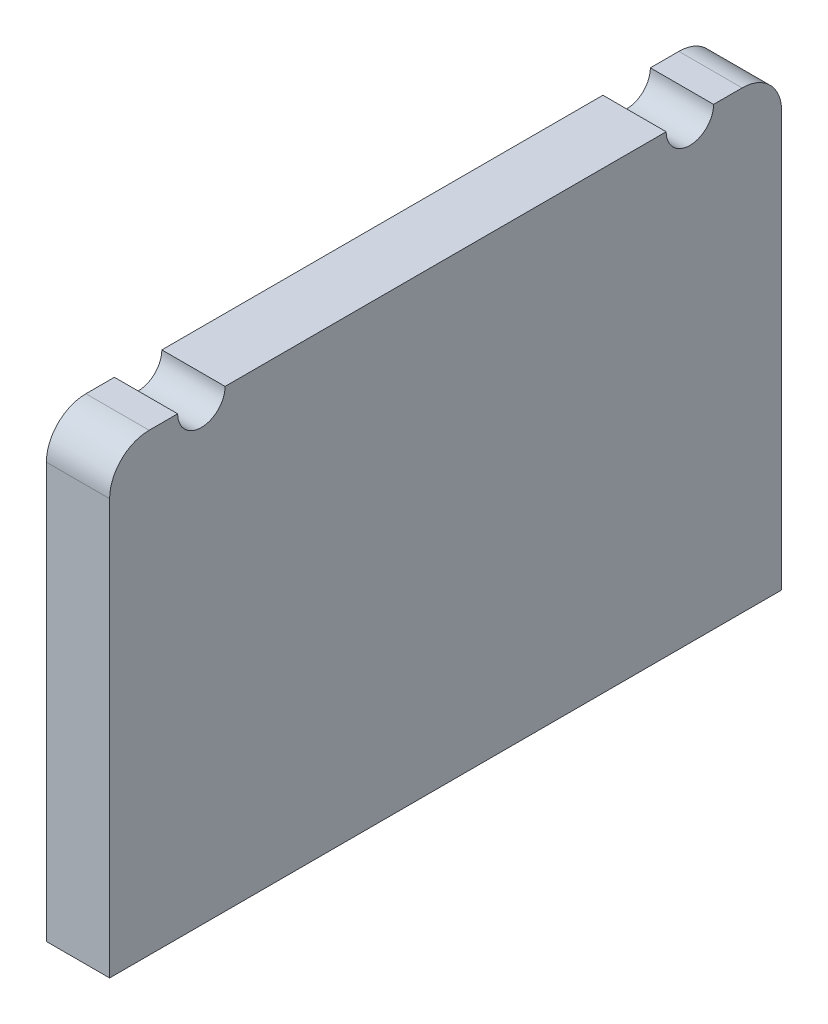
SolidWorks part; units mm, degrees
ref_plane "Front Plane" through (0, 0, 0) normal (0, 0, 1) x (1, 0, 0)
ref_plane "Top Plane" through (0, 0, 0) normal (0, 1, 0) x (1, 0, 0)
ref_plane "Right Plane" through (0, 0, 0) normal (1, 0, 0) x (0, 0, -1)
sketch "Sketch1" plane through (0, 0, 0) normal (1, 0, 0) x (0, 0, -1)
  line L1 (-53.975, -36.5125) -> (53.975, -36.5125)
  line L2 (-53.975, -36.5125) -> (-53.975, 30.1625)
  line L3 (-35.4259, 36.5125) -> (35.4259, 36.5125)
  line L4 (53.975, -36.5125) -> (53.975, 30.1625)
  line L5 (-53.975, -36.5125) -> (53.975, 36.5125) construction
  line L6 (-53.975, 36.5125) -> (53.975, -36.5125) construction
  line L7 (43.0459, 36.5125) -> (47.625, 36.5125)
  line L9 (-47.625, 36.5125) -> (-43.0459, 36.5125)
  arc A0 (47.625, 36.5125) -> (53.975, 30.1625) centre (47.625, 30.1625) cw
  arc A1 (-53.975, 30.1625) -> (-47.625, 36.5125) centre (-47.625, 30.1625) cw
  arc A2 (-43.0459, 36.5125) -> (-35.4259, 36.5125) centre (-39.2359, 36.5125) ccw
  arc A3 (35.4259, 36.5125) -> (43.0459, 36.5125) centre (39.2359, 36.5125) ccw
  point P0 (0, 0)
  point P12 (0, 36.5125)
  dimension "D1" = 6.35
  dimension "D2" = 86.0919
  dimension "D3" = 7.62
  dimension "D4" = 7.62
extrude "Boss-Extrude1" add sketch "Sketch1" along normal blind 10.16
